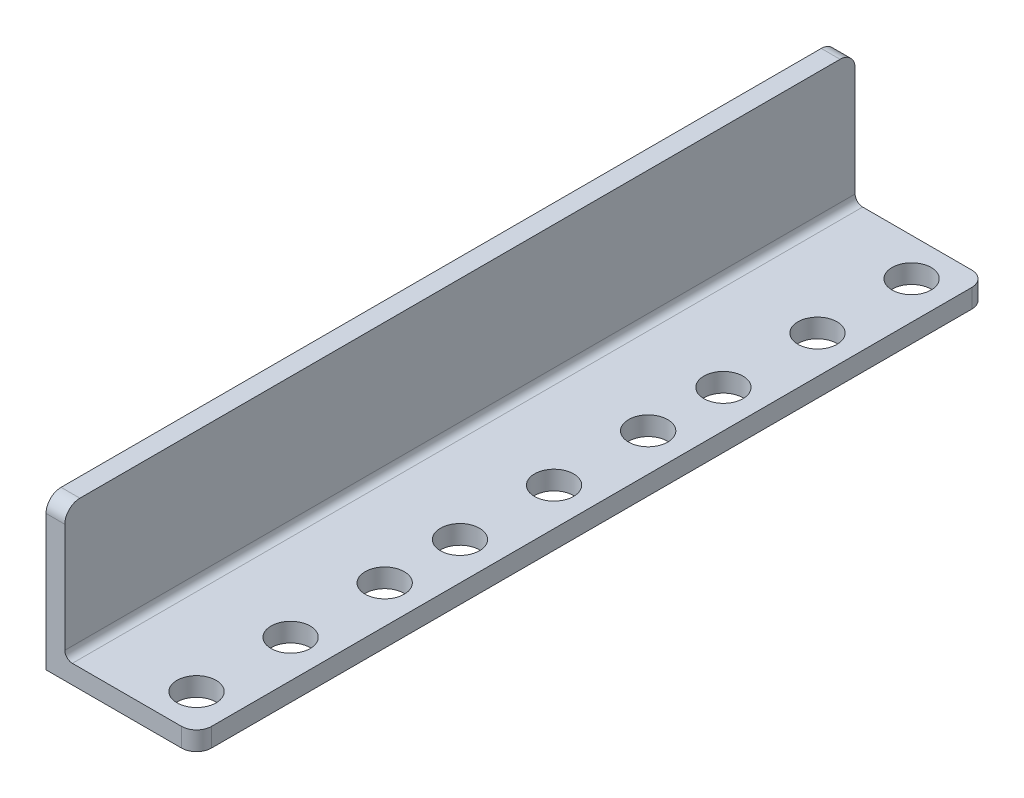
SolidWorks part; units mm, degrees
material "ASTM A36 Steel"
ref_plane "Front Plane" through (0, 0, 0) normal (0, 0, 1) x (1, 0, 0)
ref_plane "Top Plane" through (0, 0, 0) normal (0, 1, 0) x (1, 0, 0)
ref_plane "Right Plane" through (0, 0, 0) normal (1, 0, 0) x (0, 0, -1)
sketch "Sketch1" plane through (0, 0, 0) normal (0, 0, 1) x (1, 0, 0)
  line L6 (0, 0) -> (0, 25.4)
  line L7 (0, 25.4) -> (3.175, 25.4)
  line L8 (3.175, 25.4) -> (3.175, 4.445)
  line L9 (4.445, 3.175) -> (25.4, 3.175)
  line L10 (25.4, 3.175) -> (25.4, 0)
  line L11 (25.4, 0) -> (0, 0)
  arc A3 (4.445, 3.175) -> (3.175, 4.445) centre (4.445, 4.445) cw
  dimension "D3" = 3.175
  dimension "D4" = 3.175
  dimension "D5" = 1.27
  dimension "D1" = 25.4
  dimension "D2" = 25.4
extrude "Boss-Extrude1" add sketch "Sketch1" along normal mid plane 133.35
hole_wizard "M6 Clearance Hole3" positions "Sketch3" profile "Sketch4" hole size "M6" standard "ANSI Metric" end condition up to next
sketch "Sketch3" plane through (0, 0, 0) normal (0, 1, 0) x (1, 0, 0)
  line L0 (19.05, -66.675) -> (19.05, 66.675) construction
  line L4 (0, -66.675) -> (25.4, -66.675) construction
  line L5 (25.4, -66.675) -> (25.4, 66.675) construction
  line L7 (8.89, -66.675) -> (8.89, 66.675) construction
  line L8 (0, 66.675) -> (25.4, 66.675) construction
  point P0 (19.05, -60.325)
  point P2 (19.05, -44.45)
  point P4 (19.05, -28.575)
  dimension "D1" = 15.875
  dimension "D2" = 15.875
  dimension "D3" = 6.35
  dimension "D4" = 6.35
  dimension "D5" = 16.51
sketch "Sketch4" plane through (19.05, 0, 60.325) normal (1, 0, 0) x (0, 0, -1)
  line L0 (0, 0) -> (0, 3.175)
  line L1 (0, 3.175) -> (3.3, 3.175)
  line L2 (3.3, 3.175) -> (3.3, 0)
  line L5 (3.3, 0) -> (0, 0)
  line L11 (0, -6.35) -> (0, 107.95) construction
  dimension "Thru Hole Dia." = 6.6
  dimension "Thru Hole Depth" = 3.175
pattern_linear "LPattern1" count 3 spacing 44.45 along (0, 0, -1) of "M6 Clearance Hole3"
hole_wizard "M6 Clearance Hole2" positions "Sketch6" profile "Sketch7" hole size "M6" standard "ANSI Metric"
sketch "Sketch6" plane through (0, 0, 0) normal (0, 1, 0) x (1, 0, 0)
  line L0 (19.05, 66.675) -> (19.05, -66.675) construction
  line L3 (0, -66.675) -> (25.4, -66.675) construction
  line L4 (0, 66.675) -> (25.4, 66.675) construction
  line L5 (25.4, -66.675) -> (25.4, 66.675) construction
  line L6 (8.89, -66.675) -> (8.89, 66.675) construction
  point P0 (19.05, -44.45)
  point P2 (19.05, 44.45)
  point P4 (19.05, -28.575)
  dimension "D1" = 22.225
  dimension "D2" = 38.1
  dimension "D3" = 22.225
  dimension "D4" = 6.35
  dimension "D5" = 16.51
sketch "Sketch7" plane through (19.05, 0, 44.45) normal (1, 0, 0) x (0, 0, -1)
  line L0 (0, 0) -> (0, 3.175)
  line L1 (0, 3.175) -> (3.3, 3.175)
  line L2 (3.3, 3.175) -> (3.3, 0)
  line L5 (3.3, 0) -> (0, 0)
  line L11 (0, -6.35) -> (0, 107.95) construction
  dimension "Thru Hole Dia." = 6.6
  dimension "Thru Hole Depth" = 1.524
hole_wizard "M6 Clearance Hole1" positions "Sketch8" profile "Sketch9" hole size "M6" standard "ANSI Metric"
sketch "Sketch8" plane through (0, 0, 0) normal (0, 1, 0) x (1, 0, 0)
  line L0 (19.05, 66.675) -> (19.05, -66.675) construction
  line L3 (0, -66.675) -> (25.4, -66.675) construction
  line L4 (0, 66.675) -> (25.4, 66.675) construction
  line L5 (25.4, -66.675) -> (25.4, 66.675) construction
  line L6 (8.89, -66.675) -> (8.89, 66.675) construction
  point P0 (19.05, 44.45)
  point P2 (19.05, 28.575)
  point P4 (19.05, -44.45)
  dimension "D1" = 22.225
  dimension "D2" = 38.1
  dimension "D3" = 22.225
  dimension "D4" = 6.35
  dimension "D5" = 16.51
sketch "Sketch9" plane through (12.7, 0, -44.45) normal (1, 0, 0) x (0, 0, -1)
  line L0 (0, 0) -> (0, 1.5875)
  line L1 (0, 1.5875) -> (3.3, 1.5875)
  line L2 (3.3, 1.5875) -> (3.3, 0)
  line L5 (3.3, 0) -> (0, 0)
  line L11 (0, -6.35) -> (0, 107.95) construction
  dimension "Thru Hole Dia." = 6.6
  dimension "Thru Hole Depth" = 1.524
fillet "Fillet1" radius 2.54 4 edges at (25.4, 1.5875, 66.675) (1.5875, 25.4, 66.675) (25.4, 1.5875, -66.675) (1.5875, 25.4, -66.675)
equation "\"D1@Sketch3\"=\"D2@Sketch3\""
